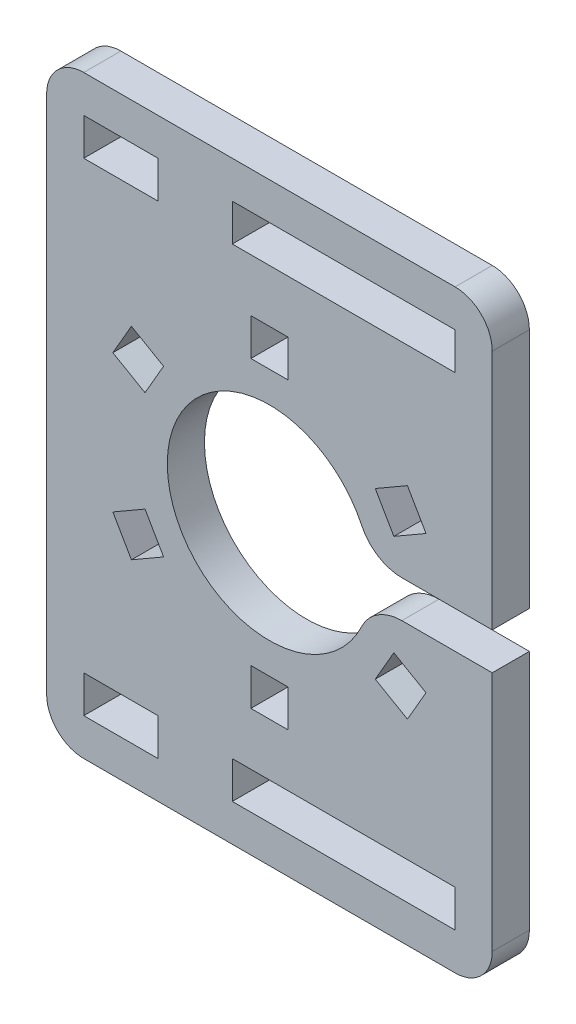
SolidWorks part; units mm, degrees
ref_plane "Plan de face" through (0, 0, 0) normal (0, 0, 1) x (1, 0, 0)
ref_plane "Plan de dessus" through (0, 0, 0) normal (0, 1, 0) x (1, 0, 0)
ref_plane "Plan de droite" through (0, 0, 0) normal (1, 0, 0) x (0, 0, -1)
sketch "Esquisse1" plane through (0, 0, 0) normal (0, 0, 1) x (1, 0, 0)
  line L0 (-55, 80) -> (-5, 80)
  line L1 (-55, 10) -> (-45, 10)
  line L2 (-55, 10) -> (-55, 5)
  line L3 (-55, 5) -> (-45, 5)
  line L4 (-45, 10) -> (-45, 5)
  line L5 (-35, 10) -> (-5, 10)
  line L6 (-35, 10) -> (-35, 5)
  line L7 (-35, 5) -> (-5, 5)
  line L8 (-5, 10) -> (-5, 5)
  line L9 (-55, 0) -> (-5, 0)
  line L10 (-5, 70) -> (-5, 75)
  line L11 (-35, 75) -> (-5, 75)
  line L12 (-35, 70) -> (-35, 75)
  line L13 (-35, 70) -> (-5, 70)
  line L14 (-45, 70) -> (-45, 75)
  line L15 (-55, 75) -> (-45, 75)
  line L16 (-55, 70) -> (-55, 75)
  line L17 (-60, 40) -> (0, 40) construction
  line L18 (-55, 70) -> (-45, 70)
  line L43 (-60, 75) -> (-60, 5)
  line L44 (-30, 57.9) -> (-30, 40) construction
  line L45 (-32.5, 62.9) -> (-27.5, 62.9)
  line L46 (-32.5, 62.9) -> (-32.5, 57.9)
  line L47 (-32.5, 57.9) -> (-27.5, 57.9)
  line L48 (-27.5, 62.9) -> (-27.5, 57.9)
  line L49 (-11.418, 53.6151) -> (-8.918, 49.2849)
  line L50 (-11.418, 53.6151) -> (-15.7481, 51.1151)
  line L51 (-15.7481, 51.1151) -> (-13.2481, 46.7849)
  line L52 (-8.918, 49.2849) -> (-13.2481, 46.7849)
  line L53 (-8.918, 30.7151) -> (-11.418, 26.3849)
  line L54 (-8.918, 30.7151) -> (-13.2481, 33.2151)
  line L55 (-13.2481, 33.2151) -> (-15.7481, 28.8849)
  line L56 (-11.418, 26.3849) -> (-15.7481, 28.8849)
  line L57 (-27.5, 17.1) -> (-32.5, 17.1)
  line L58 (-27.5, 17.1) -> (-27.5, 22.1)
  line L59 (-27.5, 22.1) -> (-32.5, 22.1)
  line L60 (-32.5, 17.1) -> (-32.5, 22.1)
  line L61 (-48.582, 26.3849) -> (-51.082, 30.7151)
  line L62 (-48.582, 26.3849) -> (-44.2519, 28.8849)
  line L63 (-44.2519, 28.8849) -> (-46.7519, 33.2151)
  line L64 (-51.082, 30.7151) -> (-46.7519, 33.2151)
  line L65 (-51.082, 49.2849) -> (-48.582, 53.6151)
  line L66 (-51.082, 49.2849) -> (-46.7519, 46.7849)
  line L67 (-46.7519, 46.7849) -> (-44.2519, 51.1151)
  line L68 (-48.582, 53.6151) -> (-44.2519, 51.1151)
  line L69 (0, 5) -> (0, 37.5)
  line L70 (0, 42.5) -> (-12.1727, 42.5)
  line L71 (-12.1727, 37.5) -> (0, 37.5)
  line L72 (0, 42.5) -> (0, 75)
  arc A0 (-55, 0) -> (-60, 5) centre (-55, 5) cw
  arc A1 (-17.5886, 45.9177) -> (-17.5886, 34.0823) centre (-30, 40) ccw
  arc A2 (-12.1727, 37.5) -> (-17.5886, 34.0823) centre (-12.1727, 31.5) ccw
  arc A3 (-12.1727, 42.5) -> (-17.5886, 45.9177) centre (-12.1727, 48.5) cw
  arc A4 (-5, 0) -> (0, 5) centre (-5, 5) ccw
  arc A5 (-5, 80) -> (0, 75) centre (-5, 75) cw
  arc A6 (-55, 80) -> (-60, 75) centre (-55, 75) ccw
  point P19 (-60, 0)
  point P25 (0, 0)
  point P29 (0, 80)
  point P34 (-60, 80)
  point P82 (-30, 40)
  dimension "D9" = 30
  dimension "D10" = 27.5
  dimension "D17" = 6
  dimension "D14" = 5
  dimension "D2" = 60
  dimension "D3" = 5
  dimension "D4" = 10
  dimension "D5" = 5
  dimension "D6" = 80
  dimension "D7" = 30
  dimension "D8" = 10
  dimension "D11" = 17.9
  dimension "D12" = 5
  dimension "D13" = 6
  dimension "D15" = 5
extrude "Boss.-Extru.1" add sketch "Esquisse1" along normal blind 5
